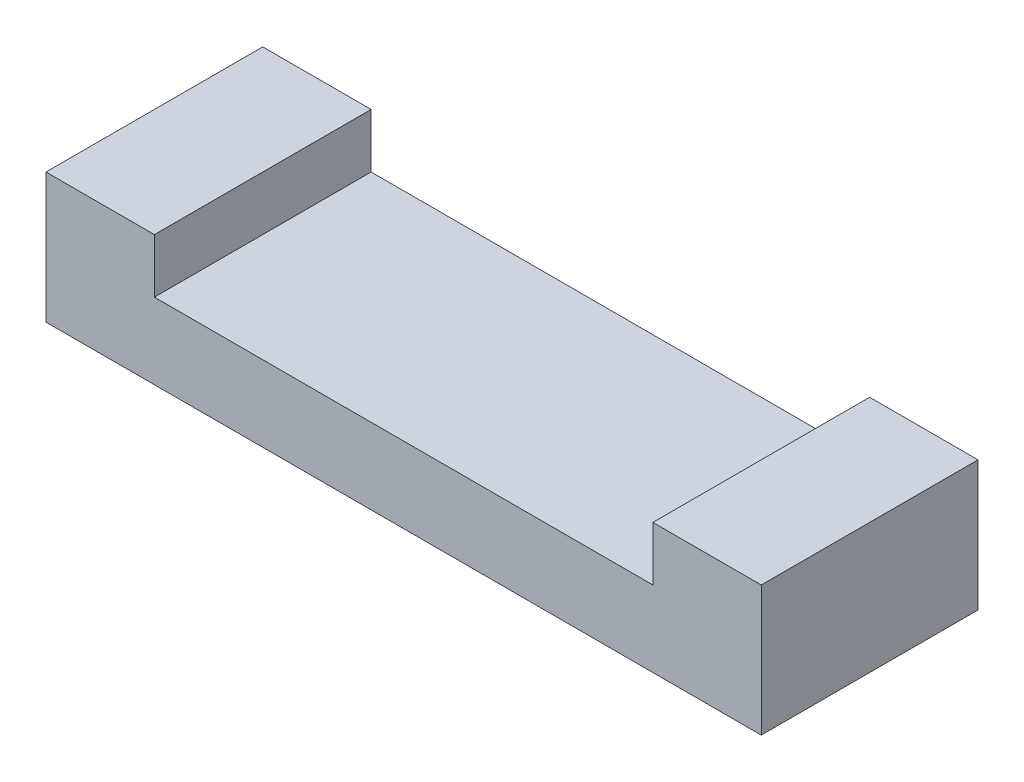
SolidWorks part; units mm, degrees
ref_plane "前视基准面" through (0, 0, 0) normal (0, 0, 1) x (1, 0, 0)
ref_plane "上视基准面" through (0, 0, 0) normal (0, 1, 0) x (1, 0, 0)
ref_plane "右视基准面" through (0, 0, 0) normal (1, 0, 0) x (0, 0, -1)
sketch "Sketch1" plane through (0, 0, 0) normal (0, 0, 1) x (1, 0, 0)
  line L0 (-17.0074, 2.5) -> (-12.0074, 2.5)
  line L1 (-12.0074, 2.5) -> (-12.0074, 0)
  line L2 (-12.0074, 0) -> (10.9926, 0)
  line L3 (10.9926, 0) -> (10.9926, 2.5)
  line L4 (10.9926, 2.5) -> (15.9926, 2.5)
  line L5 (15.9926, 2.5) -> (15.9926, -3.5)
  line L6 (15.9926, -3.5) -> (-17.0074, -3.5)
  line L7 (-17.0074, -3.5) -> (-17.0074, 2.5)
  dimension "D1" = 23
  dimension "D2" = 5
  dimension "D3" = 5
  dimension "D4" = 3.5
  dimension "D5" = 6
extrude "Extrude1" add sketch "Sketch1" along normal blind 10
